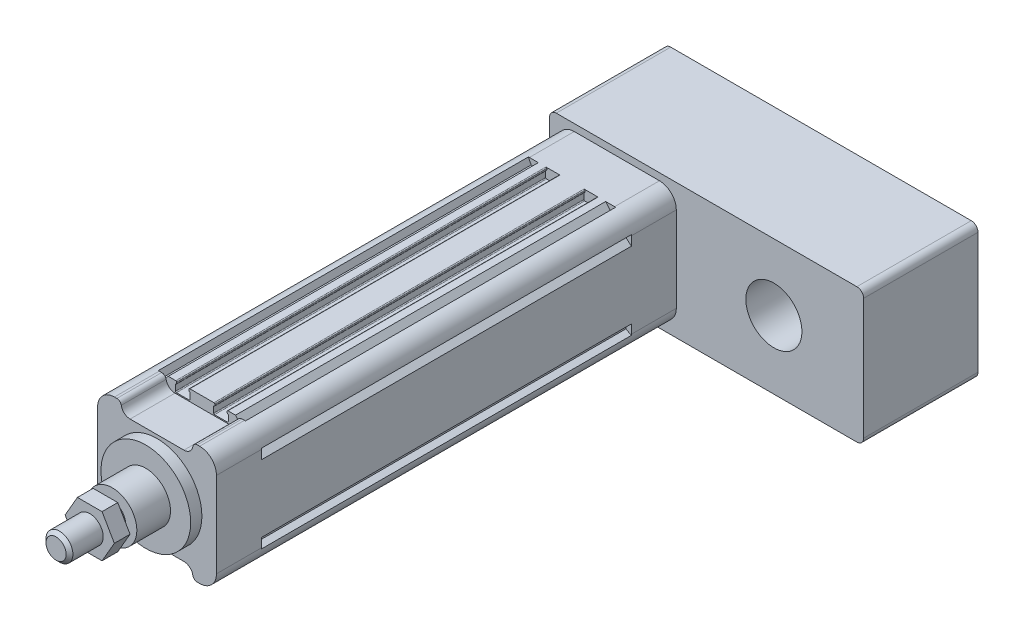
SolidWorks part; units mm, degrees
ref_plane "Front" through (0, 0, 0) normal (0, 0, 1) x (1, 0, 0)
ref_plane "Top" through (0, 0, 0) normal (0, 1, 0) x (1, 0, 0)
ref_plane "Right" through (0, 0, 0) normal (1, 0, 0) x (0, 0, -1)
sketch "草图1" plane through (0, 0, 0) normal (0, 0, 1) x (1, 0, 0)
  line L0 (19.7737, 3) -> (23.3, 3)
  line L1 (23.3, 3) -> (23.3, -3)
  line L2 (23.3, -3) -> (19.7737, -3)
  line L3 (-19.7737, -3) -> (-23.3, -3)
  line L4 (-23.3, -3) -> (-23.3, 3)
  line L5 (-23.3, 3) -> (-19.7737, 3)
  line L6 (-18.2, 24) -> (-19.4434, 26.4869)
  line L7 (-26.4869, 19.4434) -> (-24, 18.2)
  line L8 (-24, 18.2) -> (-24, 17.1)
  line L9 (-24, 17.1) -> (-26.5, 15)
  line L10 (-26.5, 15) -> (-26.5, -15)
  line L11 (-26.5, -15) -> (-24, -17.1)
  line L12 (-24, -17.1) -> (-24, -18.2)
  line L13 (-24, -18.2) -> (-26.4869, -19.4434)
  line L14 (-19.4434, -26.4869) -> (-18.2, -24)
  line L15 (-18.2, -24) -> (-17.1, -24)
  line L16 (-17.1, -24) -> (-15, -26.5)
  line L17 (-15, -26.5) -> (-11.65, -26.5)
  line L18 (-11.25, -26.1) -> (-11.25, -25.6)
  line L19 (-11.65, -25.2) -> (-11.75, -25.2)
  line L20 (-11.75, -25.2) -> (-11.75, -22.4)
  line L21 (-11.35, -22) -> (-5.65, -22)
  line L22 (-5.25, -22.4) -> (-5.25, -25.2)
  line L23 (-5.25, -25.2) -> (-5.35, -25.2)
  line L24 (-5.75, -25.6) -> (-5.75, -26.1)
  line L25 (-5.35, -26.5) -> (5.35, -26.5)
  line L26 (5.75, -26.1) -> (5.75, -25.6)
  line L27 (5.35, -25.2) -> (5.25, -25.2)
  line L28 (5.25, -25.2) -> (5.25, -22.4)
  line L29 (5.65, -22) -> (11.35, -22)
  line L30 (11.75, -22.4) -> (11.75, -25.2)
  line L31 (11.75, -25.2) -> (11.65, -25.2)
  line L32 (11.25, -25.6) -> (11.25, -26.1)
  line L33 (11.65, -26.5) -> (15, -26.5)
  line L34 (15, -26.5) -> (17.1, -24)
  line L35 (17.1, -24) -> (18.2, -24)
  line L36 (18.2, -24) -> (19.4434, -26.4869)
  line L37 (26.4869, -19.4434) -> (24, -18.2)
  line L38 (24, -18.2) -> (24, -17.1)
  line L39 (24, -17.1) -> (26.5, -15)
  line L40 (26.5, -15) -> (26.5, 15)
  line L41 (26.5, 15) -> (24, 17.1)
  line L42 (24, 17.1) -> (24, 18.2)
  line L43 (24, 18.2) -> (26.4869, 19.4434)
  line L44 (19.4434, 26.4869) -> (18.2, 24)
  line L45 (18.2, 24) -> (17.1, 24)
  line L46 (17.1, 24) -> (15, 26.5)
  line L47 (15, 26.5) -> (11.65, 26.5)
  line L48 (11.25, 26.1) -> (11.25, 25.6)
  line L49 (11.65, 25.2) -> (11.75, 25.2)
  line L50 (11.75, 25.2) -> (11.75, 22.4)
  line L51 (11.35, 22) -> (5.65, 22)
  line L52 (5.25, 22.4) -> (5.25, 25.2)
  line L53 (5.25, 25.2) -> (5.35, 25.2)
  line L54 (5.75, 25.6) -> (5.75, 26.1)
  line L55 (5.35, 26.5) -> (-5.35, 26.5)
  line L56 (-5.75, 26.1) -> (-5.75, 25.6)
  line L57 (-5.35, 25.2) -> (-5.25, 25.2)
  line L58 (-5.25, 25.2) -> (-5.25, 22.4)
  line L59 (-5.65, 22) -> (-11.35, 22)
  line L60 (-11.75, 22.4) -> (-11.75, 25.2)
  line L61 (-11.75, 25.2) -> (-11.65, 25.2)
  line L62 (-11.25, 25.6) -> (-11.25, 26.1)
  line L63 (-11.65, 26.5) -> (-15, 26.5)
  line L64 (-15, 26.5) -> (-17.1, 24)
  line L65 (-17.1, 24) -> (-18.2, 24)
  arc A0 (19.7737, 3) -> (-19.7737, 3) centre (0, 0) ccw
  arc A1 (-19.7737, -3) -> (19.7737, -3) centre (0, 0) ccw
  circle A2 centre (19, 19) radius 2.1
  circle A3 centre (19, -19) radius 2.1
  circle A4 centre (-19, -19) radius 2.1
  circle A5 centre (-19, 19) radius 2.1
  arc A6 (-19.4434, 26.4869) -> (-26.4869, 19.4434) centre (-19, 19) ccw
  arc A7 (-26.4869, -19.4434) -> (-19.4434, -26.4869) centre (-19, -19) ccw
  arc A8 (-11.65, -26.5) -> (-11.25, -26.1) centre (-11.65, -26.1) ccw
  arc A9 (-11.25, -25.6) -> (-11.65, -25.2) centre (-11.65, -25.6) ccw
  arc A10 (-11.35, -22) -> (-11.75, -22.4) centre (-11.35, -22.4) ccw
  arc A11 (-5.25, -22.4) -> (-5.65, -22) centre (-5.65, -22.4) ccw
  arc A12 (-5.35, -25.2) -> (-5.75, -25.6) centre (-5.35, -25.6) ccw
  arc A13 (-5.75, -26.1) -> (-5.35, -26.5) centre (-5.35, -26.1) ccw
  arc A14 (5.35, -26.5) -> (5.75, -26.1) centre (5.35, -26.1) ccw
  arc A15 (5.75, -25.6) -> (5.35, -25.2) centre (5.35, -25.6) ccw
  arc A16 (5.65, -22) -> (5.25, -22.4) centre (5.65, -22.4) ccw
  arc A17 (11.75, -22.4) -> (11.35, -22) centre (11.35, -22.4) ccw
  arc A18 (11.65, -25.2) -> (11.25, -25.6) centre (11.65, -25.6) ccw
  arc A19 (11.25, -26.1) -> (11.65, -26.5) centre (11.65, -26.1) ccw
  arc A20 (19.4434, -26.4869) -> (26.4869, -19.4434) centre (19, -19) ccw
  arc A21 (26.4869, 19.4434) -> (19.4434, 26.4869) centre (19, 19) ccw
  arc A22 (11.65, 26.5) -> (11.25, 26.1) centre (11.65, 26.1) ccw
  arc A23 (11.25, 25.6) -> (11.65, 25.2) centre (11.65, 25.6) ccw
  arc A24 (11.35, 22) -> (11.75, 22.4) centre (11.35, 22.4) ccw
  arc A25 (5.25, 22.4) -> (5.65, 22) centre (5.65, 22.4) ccw
  arc A26 (5.35, 25.2) -> (5.75, 25.6) centre (5.35, 25.6) ccw
  arc A27 (5.75, 26.1) -> (5.35, 26.5) centre (5.35, 26.1) ccw
  arc A28 (-5.35, 26.5) -> (-5.75, 26.1) centre (-5.35, 26.1) ccw
  arc A29 (-5.75, 25.6) -> (-5.35, 25.2) centre (-5.35, 25.6) ccw
  arc A30 (-5.65, 22) -> (-5.25, 22.4) centre (-5.65, 22.4) ccw
  arc A31 (-11.75, 22.4) -> (-11.35, 22) centre (-11.35, 22.4) ccw
  arc A32 (-11.65, 25.2) -> (-11.25, 25.6) centre (-11.65, 25.6) ccw
  arc A33 (-11.25, 26.1) -> (-11.65, 26.5) centre (-11.65, 26.1) ccw
extrude "凸台-拉伸1" add sketch "草图1" along normal blind 165
sketch "草图6" plane through (0, 0, 165) normal (0, 0, 1) x (1, 0, 0)
  line L0 (0, 0) -> (19, 0) construction
  line L2 (-26.5, -19) -> (-26.5, 19)
  line L3 (-19, 26.5) -> (-17.9161, 26.5)
  line L4 (26.5, -19) -> (26.5, 19)
  line L5 (-26.5, -26.5) -> (26.5, 26.5) construction
  line L6 (-26.5, 26.5) -> (26.5, -26.5) construction
  line L7 (-12, 21.5) -> (12, 21.5)
  line L9 (19, 26.5) -> (17.9161, 26.5)
  line L10 (19, -26.5) -> (17.9161, -26.5)
  line L11 (-12, -21.5) -> (12, -21.5)
  line L12 (-19, -26.5) -> (-17.9161, -26.5)
  arc A0 (12, 21.5) -> (15.9441, 24.8333) centre (12, 25.5) ccw
  arc A1 (-15.9441, 24.8333) -> (-12, 21.5) centre (-12, 25.5) ccw
  arc A2 (-15.9441, 24.8333) -> (-17.9161, 26.5) centre (-17.9161, 24.5) ccw
  arc A3 (15.9441, 24.8333) -> (17.9161, 26.5) centre (17.9161, 24.5) cw
  arc A4 (-26.5, -19) -> (-19, -26.5) centre (-19, -19) ccw
  arc A5 (19, -26.5) -> (26.5, -19) centre (19, -19) ccw
  arc A6 (26.5, 19) -> (19, 26.5) centre (19, 19) ccw
  arc A7 (-26.5, 19) -> (-19, 26.5) centre (-19, 19) cw
  arc A8 (15.9441, -24.8333) -> (17.9161, -26.5) centre (17.9161, -24.5) ccw
  arc A9 (12, -21.5) -> (15.9441, -24.8333) centre (12, -25.5) cw
  arc A10 (-15.9441, -24.8333) -> (-12, -21.5) centre (-12, -25.5) cw
  arc A11 (-15.9441, -24.8333) -> (-17.9161, -26.5) centre (-17.9161, -24.5) cw
  point P0 (0, 0)
  point P9 (0, 21.5)
  point P13 (20, 20.8461)
  point P16 (-12, 20.8461)
  dimension "D5" = 4
  dimension "D6" = 2
  dimension "D7" = 2
  dimension "D9" = 7.5
  dimension "D1" = 53
  dimension "D2" = 53
  dimension "D3" = 26.5
  dimension "D4" = 24
  dimension "D8" = 5
extrude "凸台-拉伸2" add sketch "草图6" along normal blind 20
sketch "草图7" plane through (0, 0, 185) normal (0, 0, 1) x (1, 0, 0)
  circle A0 centre (0, 0) radius 20
  dimension "D1" = 40
extrude "凸台-拉伸3" add sketch "草图7" along normal blind 5
sketch "草图9" plane through (0, 0, 190) normal (0, 0, 1) x (1, 0, 0)
  circle A0 centre (0, 0) radius 11
  dimension "D1" = 22
extrude "凸台-拉伸4" add sketch "草图9" along normal blind 15
sketch "草图10" plane through (0, 0, 205) normal (0, 0, 1) x (1, 0, 0)
  circle A0 centre (0, 0) radius 6
  dimension "D1" = 12
extrude "凸台-拉伸5" add sketch "草图10" along normal blind 25
sketch "草图11" plane through (0, 0, 0) normal (0, 0, -1) x (-1, 0, 0)
  line L1 (-19, -26.5) -> (19, -26.5)
  line L2 (-26.5, -19) -> (-26.5, 19)
  line L3 (-19, 26.5) -> (19, 26.5)
  line L4 (26.5, -19) -> (26.5, 19)
  line L5 (-26.5, -26.5) -> (26.5, 26.5) construction
  line L6 (-26.5, 26.5) -> (26.5, -26.5) construction
  arc A0 (-26.5, -19) -> (-19, -26.5) centre (-19, -19) ccw
  arc A1 (19, -26.5) -> (26.5, -19) centre (19, -19) ccw
  arc A2 (26.5, 19) -> (19, 26.5) centre (19, 19) ccw
  arc A3 (-26.5, 19) -> (-19, 26.5) centre (-19, 19) cw
  point P0 (0, 0)
  dimension "D3" = 7.5
  dimension "D1" = 53
  dimension "D2" = 53
extrude "凸台-拉伸6" add sketch "草图11" along normal blind 20
sketch "草图12" plane through (0, 0, -20) normal (0, 0, -1) x (-1, 0, 0)
  line L1 (-107, -30.4042) -> (27, -30.4042)
  line L2 (-110, -27.4042) -> (-110, 26.5958)
  line L3 (-107, 29.5958) -> (27, 29.5958)
  line L4 (30, -27.4042) -> (30, 26.5958)
  line L5 (-110, -30.4042) -> (30, 29.5958) construction
  line L6 (-110, 29.5958) -> (30, -30.4042) construction
  arc A0 (27, 29.5958) -> (30, 26.5958) centre (27, 26.5958) cw
  arc A1 (30, -27.4042) -> (27, -30.4042) centre (27, -27.4042) cw
  arc A2 (-110, -27.4042) -> (-107, -30.4042) centre (-107, -27.4042) ccw
  arc A3 (-110, 26.5958) -> (-107, 29.5958) centre (-107, 26.5958) cw
  point P0 (-40, -0.4042)
  dimension "D4" = 3
  dimension "D1" = 60
  dimension "D2" = 140
  dimension "D3" = 30
extrude "凸台-拉伸7" add sketch "草图12" along normal blind 51
sketch "草图13" plane through (0, 0, -20) normal (0, 0, 1) x (1, 0, 0)
  circle A0 centre (70, 0) radius 12.5
  dimension "D2" = 25
  dimension "D1" = 70
extrude "切除-拉伸2" cut sketch "草图13" against normal blind 30
hole_wizard "M6 螺纹孔1" positions "草图14" profile "草图15" tap size "M6" standard "GB"
sketch "草图14" plane through (0, 0, -71) normal (0, 0, -1) x (-1, 0, 0)
  line L0 (30, -27.4042) -> (30, 26.5958) construction
  point P0 (19, -19)
  dimension "D1" = 11
  dimension "D2" = 19
sketch "草图15" plane through (-19, -19, -71) normal (1, 0, 0) x (0, 1, 0)
  line L0 (0, 0) -> (0, 16.5022)
  line L1 (0, 16.5022) -> (2.5, 15)
  line L2 (2.5, 15) -> (2.5, 0)
  line L5 (2.5, 0) -> (0, 0)
  line L10 (0, 16.5022) -> (-2.5, 15) construction
  line L11 (0, -6.35) -> (0, 107.95) construction
  dimension "螺纹孔钻头直径" = 5
  dimension "螺纹孔钻头深度" = 15
  dimension "导头角度" = 118
cosmetic thread "孔螺蚊线4" parameters "D1"=12, "D2"=6
pattern_linear "阵列(线性)1" count 2 spacing 38 along (0, 1, 0) count 2 spacing 38 along (1, 0, 0) of "M6 螺纹孔1"
hole_wizard "M6 螺纹孔2" positions "草图16" profile "草图17" tap size "M6" standard "GB"
sketch "草图16" plane through (0, 0, -71) normal (0, 0, -1) x (-1, 0, 0)
  circle A1 centre (-19, 19) radius 2.5 construction
  circle A2 centre (-19, -19) radius 2.5 construction
  point P0 (-84, -19)
  point P2 (-84, 19)
  dimension "D3" = 65
  dimension "D1" = 19
  dimension "D2" = 19
  dimension "D4" = 65
sketch "草图17" plane through (84, -19, -71) normal (1, 0, 0) x (0, 1, 0)
  line L0 (0, 0) -> (0, 16.5022)
  line L1 (0, 16.5022) -> (2.5, 15)
  line L2 (2.5, 15) -> (2.5, 0)
  line L5 (2.5, 0) -> (0, 0)
  line L10 (0, 16.5022) -> (-2.5, 15) construction
  line L11 (0, -6.35) -> (0, 107.95) construction
  dimension "螺纹孔钻头直径" = 5
  dimension "螺纹孔钻头深度" = 15
  dimension "导头角度" = 118
cosmetic thread "孔螺蚊线5" parameters "D1"=12, "D2"=6
cosmetic thread "孔螺蚊线6" parameters "D1"=12, "D2"=6
hole_wizard "M6 螺纹孔3" positions "草图19" profile "草图20" tap size "M6" standard "GB"
sketch "草图19" plane through (-26.5, 0, 0) normal (-1, 0, 0) x (0, 0, 1)
  line L0 (185, 19) -> (185, -19) construction
  point P0 (175, 11)
  point P2 (175, -11)
  dimension "D1" = 10
  dimension "D2" = 10
  dimension "D3" = 22
  dimension "D4" = 11
sketch "草图20" plane through (-26.5, 11, 175) normal (0, 1, 0) x (0, 0, 1)
  line L0 (0, 0) -> (0, 16.5022)
  line L1 (0, 16.5022) -> (2.5, 15)
  line L2 (2.5, 15) -> (2.5, 0)
  line L5 (2.5, 0) -> (0, 0)
  line L10 (0, 16.5022) -> (-2.5, 15) construction
  line L11 (0, -6.35) -> (0, 107.95) construction
  dimension "螺纹孔钻头直径" = 5
  dimension "螺纹孔钻头深度" = 15
  dimension "导头角度" = 118
cosmetic thread "孔螺蚊线7" parameters "D1"=12, "D2"=6
cosmetic thread "孔螺蚊线8" parameters "D1"=12, "D2"=6
hole_wizard "M6 螺纹孔4" positions "草图21" profile "草图22" tap size "M6" standard "GB"
sketch "草图21" plane through (-26.5, 0, 0) normal (-1, 0, 0) x (0, 0, 1)
  line L0 (-20, -27.4042) -> (-20, 26.5958) construction
  line L1 (-20, -19) -> (-20, 19) construction
  point P0 (-10, 11)
  point P2 (-10, -11)
  dimension "D1" = 10
  dimension "D2" = 10
  dimension "D3" = 11
  dimension "D4" = 11
sketch "草图22" plane through (-26.5, 11, -10) normal (0, 1, 0) x (0, 0, 1)
  line L0 (0, 0) -> (0, 16.5022)
  line L1 (0, 16.5022) -> (2.5, 15)
  line L2 (2.5, 15) -> (2.5, 0)
  line L5 (2.5, 0) -> (0, 0)
  line L10 (0, 16.5022) -> (-2.5, 15) construction
  line L11 (0, -6.35) -> (0, 107.95) construction
  dimension "螺纹孔钻头直径" = 5
  dimension "螺纹孔钻头深度" = 15
  dimension "导头角度" = 118
cosmetic thread "孔螺蚊线9" parameters "D1"=12, "D2"=6
cosmetic thread "孔螺蚊线10" parameters "D1"=12, "D2"=6
chamfer "倒角1" distance 1.5 angle 45 1 edges at (6, 0, 230)
sketch "草图23" plane through (0, 0, 205) normal (0, 0, 1) x (1, 0, 0)
  line L1 (10.9697, 0) -> (5.4848, 9.5)
  line L2 (5.4848, 9.5) -> (-5.4848, 9.5)
  line L3 (-5.4848, 9.5) -> (-10.9697, 0)
  line L4 (-10.9697, 0) -> (-5.4848, -9.5)
  line L5 (-5.4848, -9.5) -> (5.4848, -9.5)
  line L6 (5.4848, -9.5) -> (10.9697, 0)
  circle A0 centre (0, 0) radius 9.5 construction
  dimension "D1" = 19
extrude "凸台-拉伸8" add sketch "草图23" along normal blind 7 from offset 3
